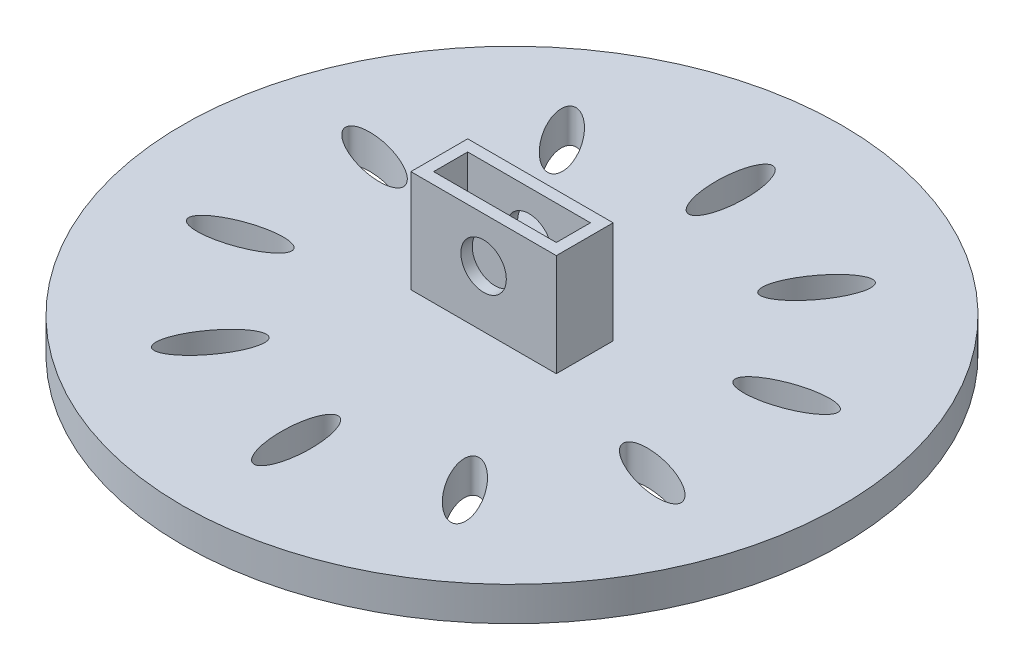
SolidWorks part; units mm, degrees
material "AISI 1020"
ref_plane "Front Plane" through (0, 0, 0) normal (0, 0, 1) x (1, 0, 0)
ref_plane "Top Plane" through (0, 0, 0) normal (0, 1, 0) x (1, 0, 0)
ref_plane "Right Plane" through (0, 0, 0) normal (1, 0, 0) x (0, 0, -1)
sketch "Sketch2" plane through (0, 0, 0) normal (0, 1, 0) x (1, 0, 0)
  circle A0 centre (0, 0) radius 145
  ellipse E0 centre (0, -95) end of major axis (0, -76.5) minor radius 6.5
  ellipse E1 centre (-56.0833, -76.6789) end of major axis (-66.9573, -91.6458) minor radius 6.5
  ellipse E2 centre (-90.6868, -28.892) end of major axis (-73.0923, -23.1751) minor radius 6.5
  ellipse E3 centre (-90.5932, 30.108) end of major axis (-108.1877, 35.8248) minor radius 6.5
  ellipse E4 centre (-55.8381, 77.7849) end of major axis (-66.7122, 92.7517) minor radius 6.5
  ellipse E5 centre (0.3031, 95.9278) end of major axis (0.3031, 77.4278) minor radius 6.5
  ellipse E6 centre (56.3864, 77.6067) end of major axis (45.5124, 62.6399) minor radius 6.5
  ellipse E7 centre (90.9899, 29.8197) end of major axis (73.3954, 24.1029) minor radius 6.5
  ellipse E8 centre (90.8963, -29.1802) end of major axis (73.3017, -23.4634) minor radius 6.5
  ellipse E9 centre (56.1412, -76.8571) end of major axis (67.0152, -91.8239) minor radius 6.5
  point P66 (0.1515, 0.4639)
  dimension "BaseDia" = 290
  dimension "D2" = 95
  dimension "D3" = 13
  dimension "D4" = 37
  dimension "D6" = 59
  dimension "D7" = 95
  dimension "D5" = 10
extrude "Boss-Extrude1" add sketch "Sketch2" along normal blind 15
sketch "Sketch3" plane through (0, 15, 0) normal (0, 1, 0) x (1, 0, 0)
  line L0 (-32, 12.5) -> (32, 12.5)
  line L1 (-27, -7.5) -> (27, -7.5)
  line L2 (-27, -7.5) -> (-27, 7.5)
  line L3 (-27, 7.5) -> (27, 7.5)
  line L4 (27, -7.5) -> (27, 7.5)
  line L5 (-27, -7.5) -> (27, 7.5) construction
  line L6 (-27, 7.5) -> (27, -7.5) construction
  line L7 (32, -12.5) -> (32, 12.5)
  line L8 (-32, -12.5) -> (32, -12.5)
  line L9 (-32, -12.5) -> (-32, 12.5)
  point P0 (0, 0)
  dimension "D1" = 15
  dimension "D2" = 54
  dimension "D3" = 5
shell "Shell4" thickness 10
extrude "Boss-Extrude2" add sketch "Sketch3" along normal blind 45
sketch "Sketch5" plane through (0, 0, 0) normal (0, 0, 1) x (1, 0, 0)
  line L0 (0, 60) -> (0, 50060) construction
  line L1 (-32, 60) -> (32, 60) construction
  line L2 (-32, 37.5) -> (-50032, 37.5) construction
  line L3 (-32, 60) -> (-32, 15) construction
  line L4 (-32, 15) -> (32, 15) construction
  circle A0 centre (0, 40) radius 10
  point P6 (0, 60)
  point P11 (-32, 37.5)
  dimension "D1" = 20
  dimension "D2" = 25
extrude "Cut-Extrude2" cut sketch "Sketch5" against normal through all and the other way through all
equation "\"BaseDiameter\"= 290mm"
equation "\"BaseDia@Sketch2\" = \"BaseDiameter\""
equation "\"D4@Sketch2\"= \"BaseDiameter\" * 37 / 290"
equation "\"D3@Sketch2\"= \"BaseDiameter\" * 13 / 290"
equation "\"D6@Sketch2\"= \"BaseDiameter\" * 59 / 290"
